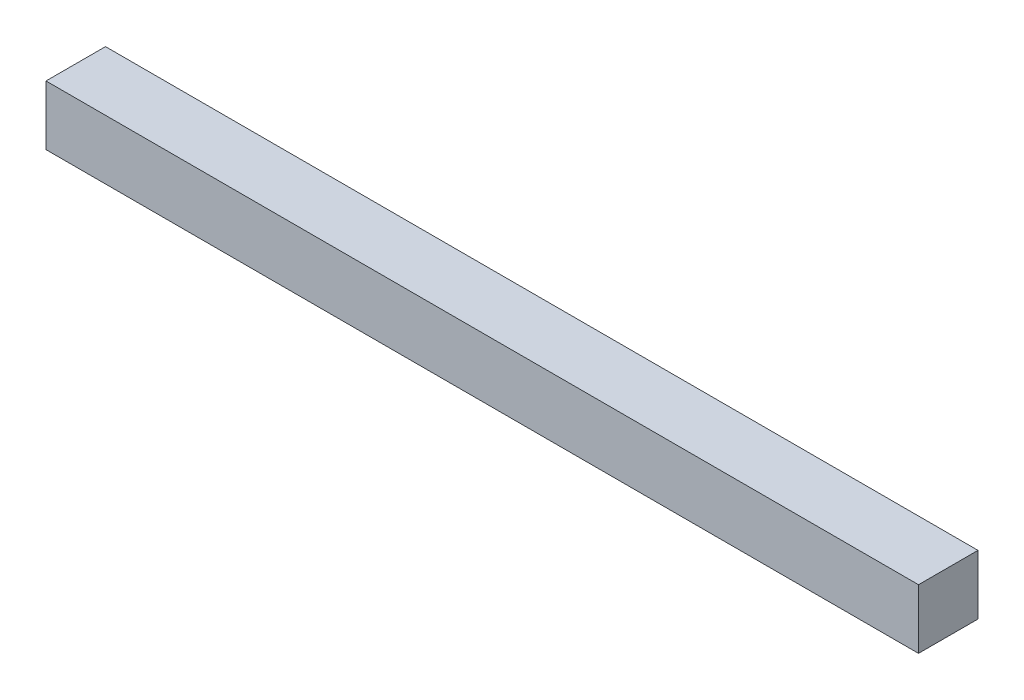
SolidWorks part; units mm, degrees
ref_plane "前视" through (0, 0, 0) normal (0, 0, 1) x (1, 0, 0)
ref_plane "上视" through (0, 0, 0) normal (0, 1, 0) x (1, 0, 0)
ref_plane "右视" through (0, 0, 0) normal (1, 0, 0) x (0, 0, -1)
sketch "草图1" plane through (0, 0, 0) normal (0, 0, 1) x (1, 0, 0)
  line L1 (0, 150) -> (2200, 150)
  line L2 (0, 150) -> (0, 0)
  line L3 (0, 0) -> (2200, 0)
  line L4 (2200, 150) -> (2200, 0)
  dimension "D1" = 2200
  dimension "D2" = 150
extrude "基体-拉伸" add sketch "草图1" along normal blind 150
